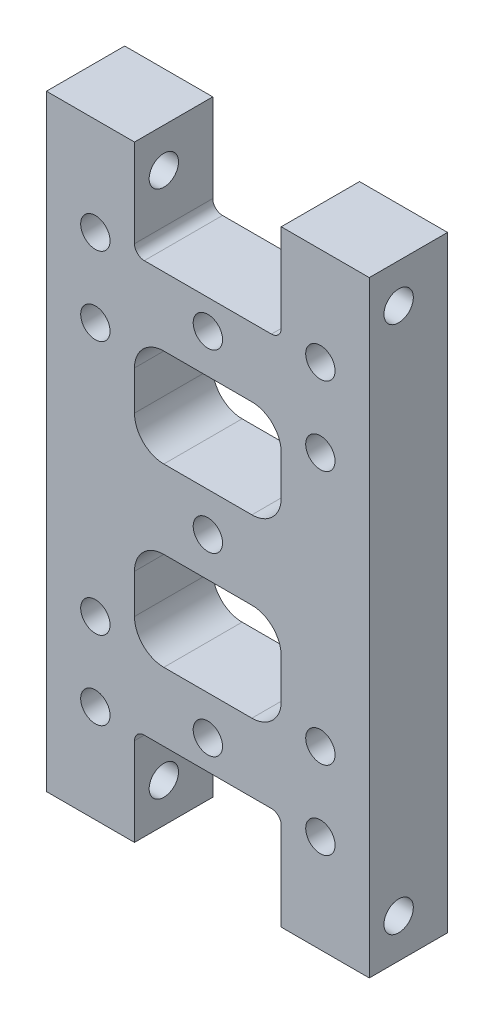
SolidWorks part; units mm, degrees
material "POM 乙缩醛共聚物"
ref_plane "前视基准面" through (0, 0, 0) normal (0, 0, 1) x (1, 0, 0)
ref_plane "上视基准面" through (0, 0, 0) normal (0, 1, 0) x (1, 0, 0)
ref_plane "右视基准面" through (0, 0, 0) normal (1, 0, 0) x (0, 0, -1)
sketch "草图1" plane through (0, 0, 0) normal (0, 0, 1) x (1, 0, 0)
  line L0 (-16.5, -31) -> (16.5, -31)
  line L1 (-16.5, -31) -> (-16.5, 31)
  line L2 (-16.5, 31) -> (16.5, 31)
  line L3 (16.5, -31) -> (16.5, 31)
  line L4 (-16.5, -31) -> (16.5, 31) construction
  line L5 (-16.5, 31) -> (16.5, -31) construction
  point P0 (0, 0)
  dimension "D1" = 33
  dimension "D2" = 62
extrude "凸台-拉伸1" add sketch "草图1" along normal blind 8
sketch "草图2" plane through (0, 0, 8) normal (0, 0, 1) x (1, 0, 0)
  line L0 (0, 31) -> (0, -31) construction
  line L1 (16.5, 31) -> (-16.5, 31) construction
  line L2 (-16.5, -31) -> (16.5, -31) construction
  line L3 (-16.5, 0) -> (16.5, 0) construction
  line L4 (-16.5, 31) -> (-16.5, -31) construction
  line L5 (16.5, -31) -> (16.5, 31) construction
  line L18 (-7.5, -31) -> (7.5, -21) construction
  line L19 (-7.5, 21) -> (7.5, 21)
  line L20 (-7.5, 21) -> (-7.5, 31)
  line L21 (-7.5, 31) -> (7.5, 31)
  line L22 (7.5, 21) -> (7.5, 31)
  line L23 (-7.5, 21) -> (7.5, 31) construction
  line L24 (-7.5, 31) -> (7.5, 21) construction
  line L25 (-7.5, -21) -> (7.5, -31) construction
  line L26 (7.5, -21) -> (7.5, -31)
  line L27 (-7.5, -31) -> (7.5, -31)
  line L28 (-7.5, -21) -> (-7.5, -31)
  line L29 (-7.5, -21) -> (7.5, -21)
  point P22 (0, 26)
  point P31 (0, -26)
  dimension "D1" = 7.5
  dimension "D4" = 10
extrude "切除-拉伸1" cut sketch "草图2" against normal through all
sketch "草图3" plane through (0, 0, 8) normal (0, 0, 1) x (1, 0, 0)
  line L0 (0, 21) -> (0, -21) construction
  line L1 (-7.5, 21) -> (7.5, 21) construction
  line L2 (7.5, -21) -> (-7.5, -21) construction
  line L3 (-16.5, 0) -> (16.5, 0) construction
  line L4 (-16.5, 31) -> (-16.5, -31) construction
  line L5 (16.5, -31) -> (16.5, 31) construction
  line L6 (11.5, 31) -> (11.5, -31) construction
  line L7 (16.5, 31) -> (7.5, 31) construction
  line L8 (7.5, -31) -> (16.5, -31) construction
  circle A1 centre (11.5, 13) radius 1.5
  circle A2 centre (11.5, 21) radius 1.5
  circle A5 centre (11.5, -21) radius 1.5
  circle A6 centre (11.5, -13) radius 1.5
  circle A7 centre (-11.5, -13) radius 1.5
  circle A8 centre (-11.5, -21) radius 1.5
  circle A11 centre (-11.5, 21) radius 1.5
  circle A12 centre (-11.5, 13) radius 1.5
  dimension "D2" = 3
  dimension "D1" = 13
  dimension "D3" = 11.5
  dimension "D4" = 8
extrude "切除-拉伸2" cut sketch "草图3" against normal through all
sketch "草图4" plane through (-16.5, 0, 0) normal (-1, 0, 0) x (0, 0, 1)
  line L0 (5, 30) -> (5, -30) construction
  line L1 (8, 31) -> (0, 31) construction
  line L3 (0, 0) -> (8, 0) construction
  line L4 (8, 31) -> (8, -31) construction
  circle A0 centre (5, 27) radius 1.5
  circle A1 centre (5, -27) radius 1.5
  dimension "D1" = 3
  dimension "D2" = 4
  dimension "D3" = 3
extrude "切除-拉伸3" cut sketch "草图4" against normal through all
fillet "圆角2" radius 1 4 edges at (-7.5, 21, 4) (7.5, 21, 4) (7.5, -21, 4) (-7.5, -21, 4)
sketch "草图5" plane through (0, 0, 0) normal (0, 0, -1) x (-1, 0, 0)
  line L0 (0, 21) -> (0, -21) construction
  line L1 (6.5, 21) -> (-6.5, 21) construction
  line L2 (-6.5, -21) -> (6.5, -21) construction
  line L3 (-16.5, 0) -> (16.5, 0) construction
  line L4 (-16.5, -31) -> (-16.5, 31) construction
  line L5 (16.5, 31) -> (16.5, -31) construction
  circle A0 centre (0, 0) radius 1.5
  circle A1 centre (0, 18) radius 1.5
  circle A2 centre (0, -18) radius 1.5
  dimension "D1" = 3
  dimension "D2" = 3
extrude "切除-拉伸4" cut sketch "草图5" against normal through all
sketch "草图7" plane through (0, 0, 0) normal (0, 0, -1) x (-1, 0, 0)
  line L0 (0, 21) -> (0, -21) construction
  line L1 (6.5, 21) -> (-6.5, 21) construction
  line L2 (-6.5, -21) -> (6.5, -21) construction
  line L3 (16.5, 0) -> (-16.5, 0) construction
  line L4 (-7.5, 14) -> (7.5, 14)
  line L5 (-7.5, 14) -> (-7.5, 4)
  line L6 (-7.5, 4) -> (7.5, 4)
  line L7 (7.5, 14) -> (7.5, 4)
  line L8 (-7.5, 14) -> (7.5, 4) construction
  line L9 (-7.5, 4) -> (7.5, 14) construction
  line L10 (16.5, 31) -> (16.5, -31) construction
  line L11 (-16.5, -31) -> (-16.5, 31) construction
  line L12 (-7.5, -4) -> (7.5, -14) construction
  line L13 (-7.5, -14) -> (7.5, -4) construction
  line L14 (7.5, -14) -> (7.5, -4)
  line L15 (-7.5, -4) -> (7.5, -4)
  line L16 (-7.5, -14) -> (-7.5, -4)
  line L17 (-7.5, -14) -> (7.5, -14)
  point P6 (0, 9)
  point P21 (0, -9)
  dimension "D1" = 10
  dimension "D2" = 15
  dimension "D3" = 9
extrude "切除-拉伸5" cut sketch "草图7" against normal through all
fillet "圆角3" radius 3 8 edges at (7.5, -14, 4) (-7.5, -14, 4) (-7.5, -4, 4) (7.5, -4, 4) (7.5, 4, 4) (-7.5, 4, 4) (-7.5, 14, 4) (7.5, 14, 4)
sketch "草图8" plane through (0, 0, 0) normal (0, 0, -1) x (-1, 0, 0)
  circle A0 centre (11.5, 21) radius 3.5
  circle A1 centre (-11.5, 21) radius 3.5
  circle A2 centre (-11.5, -21) radius 3.5
  circle A3 centre (11.5, -21) radius 3.5
  circle A4 centre (0, 0) radius 3
  dimension "D1" = 7
  dimension "D2" = 6
extrude "切除-拉伸6" cut sketch "草图8" against normal blind 3.5
